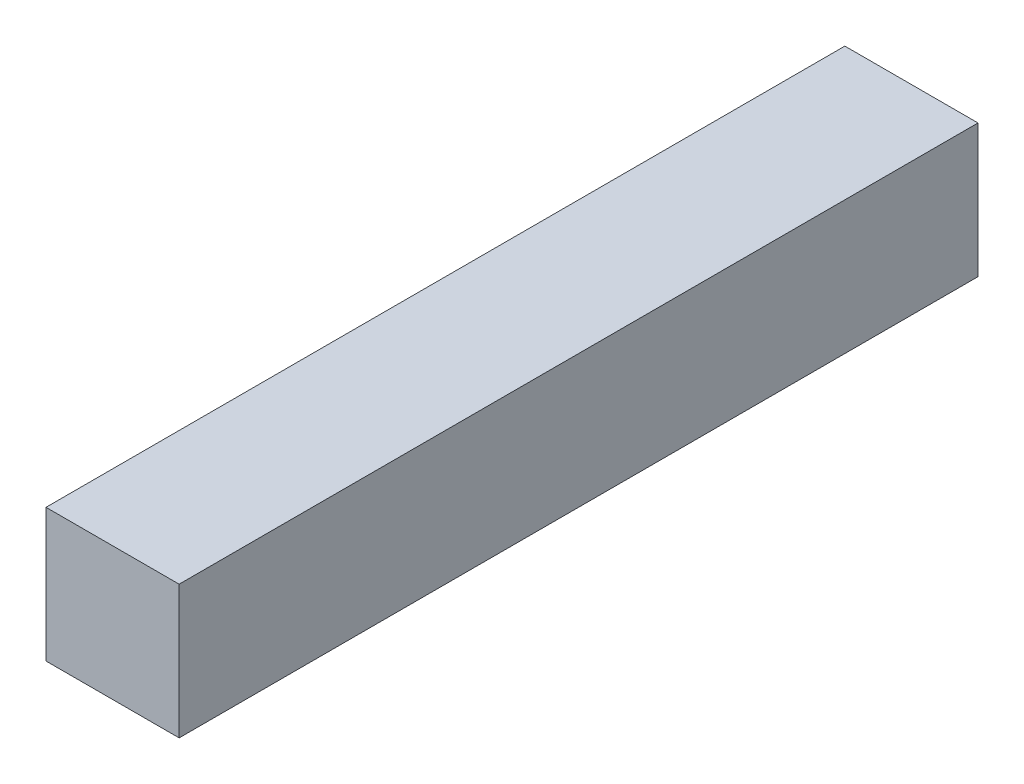
SolidWorks part; units mm, degrees
ref_plane "Front Plane" through (0, 0, 0) normal (0, 0, 1) x (1, 0, 0)
ref_plane "Top Plane" through (0, 0, 0) normal (0, 1, 0) x (1, 0, 0)
ref_plane "Right Plane" through (0, 0, 0) normal (1, 0, 0) x (0, 0, -1)
sketch "Sketch7" plane through (0, 0, 0) normal (0, 0, 1) x (1, 0, 0)
  line L1 (-12.7, -12.7) -> (12.7, -12.7)
  line L2 (-12.7, -12.7) -> (-12.7, 12.7)
  line L3 (-12.7, 12.7) -> (12.7, 12.7)
  line L4 (12.7, -12.7) -> (12.7, 12.7)
  line L5 (-12.7, -12.7) -> (12.7, 12.7) construction
  line L6 (-12.7, 12.7) -> (12.7, -12.7) construction
  point P0 (0, 0)
  dimension "D1" = 25.4
extrude "Boss-Extrude3" add sketch "Sketch7" along normal mid plane 152.4
